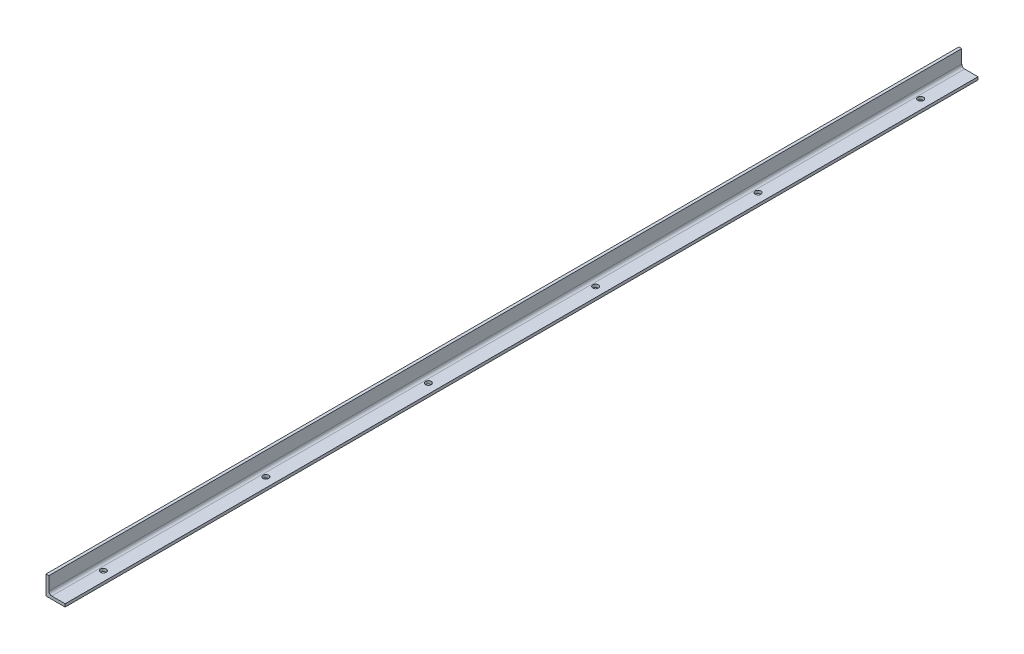
SolidWorks part; units mm, degrees
ref_plane "Plan de face" through (0, 0, 0) normal (0, 0, 1) x (1, 0, 0)
ref_plane "Plan de dessus" through (0, 0, 0) normal (0, 1, 0) x (1, 0, 0)
ref_plane "Plan de droite" through (0, 0, 0) normal (1, 0, 0) x (0, 0, -1)
sketch "Esquisse1" plane through (0, 0, 0) normal (0, 0, 1) x (1, 0, 0)
  line L0 (0, 0) -> (0, 20)
  line L1 (0, 20) -> (3, 20)
  line L2 (3, 20) -> (3, 6)
  line L3 (6, 3) -> (20, 3)
  line L4 (20, 3) -> (20, 0)
  line L5 (20, 0) -> (0, 0)
  arc A0 (3, 6) -> (6, 3) centre (6, 6) ccw
  dimension "D5" = 3
  dimension "D1" = 20
  dimension "D2" = 20
  dimension "D3" = 3
  dimension "D4" = 3
extrude "Boss.-Extru.1" add sketch "Esquisse1" along normal blind 955
sketch "Esquisse2" plane through (0, 0, 0) normal (0, -1, 0) x (-1, 0, 0)
  line L0 (0, 0) -> (-20, 0) construction
  line L1 (0, -955) -> (-20, -955) construction
  line L4 (0, -955) -> (0, 0) construction
  circle A0 centre (-10, -50) radius 3
  circle A1 centre (-10, -905) radius 3
  circle A2 centre (-10, -220) radius 3
  circle A3 centre (-10, -735) radius 3
  circle A4 centre (-10, -390) radius 3
  circle A5 centre (-10, -565) radius 3
  point P10 (-10, 0)
  dimension "D1" = 6
  dimension "D2" = 6
  dimension "D9" = 6
  dimension "D10" = 6
  dimension "D13" = 10
  dimension "D15" = 6
  dimension "D16" = 6
  dimension "D3" = 50
  dimension "D4" = 955
  dimension "D5" = 855
  dimension "D6" = 50
  dimension "D7" = 10
  dimension "D8" = 10
  dimension "D11" = 170
  dimension "D12" = 170
  dimension "D14" = 10
  dimension "D17" = 170
  dimension "D18" = 170
extrude "Enlèv. mat.-Extru.1" cut sketch "Esquisse2" against normal blind 955
